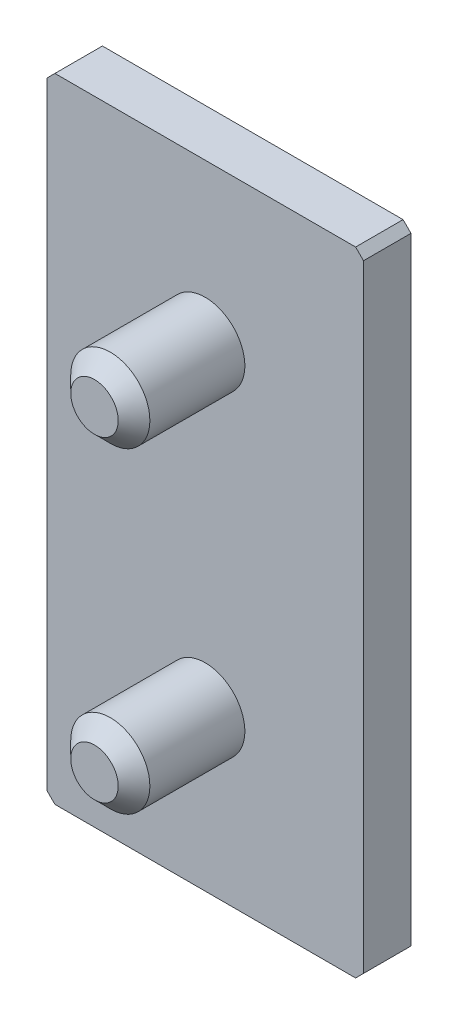
SolidWorks part; units mm, degrees
ref_plane "Front Plane" through (0, 0, 0) normal (0, 0, 1) x (1, 0, 0)
ref_plane "Top Plane" through (0, 0, 0) normal (0, 1, 0) x (1, 0, 0)
ref_plane "Right Plane" through (0, 0, 0) normal (1, 0, 0) x (0, 0, -1)
sketch "Sketch1" plane through (0, 0, 0) normal (0, 0, 1) x (1, 0, 0)
  line L1 (0, 0) -> (20, 0)
  line L2 (0, 0) -> (0, 40)
  line L3 (0, 40) -> (20, 40)
  line L4 (20, 0) -> (20, 40)
  dimension "D1" = 20
  dimension "D2" = 40
extrude "Boss-Extrude1" add sketch "Sketch1" along normal blind 3
sketch "Sketch2" plane through (0, 0, 3) normal (0, 0, 1) x (1, 0, 0)
  line L0 (20, 40) -> (0, 40) construction
  line L1 (20, 0) -> (20, 40) construction
  line L2 (0, 0) -> (20, 0) construction
  line L3 (0, 40) -> (0, 0) construction
  circle A0 centre (10, 30) radius 2.5
  circle A1 centre (10, 10) radius 2.5
  dimension "D1" = 10
  dimension "D6" = 5
  dimension "D7" = 5
  dimension "D2" = 10
  dimension "D3" = 10
  dimension "D4" = 10
  dimension "D5" = 20
extrude "Boss-Extrude2" add sketch "Sketch2" along normal blind 7
chamfer "Chamfer1" distance 1 angle 45 2 edges at (12.5, 10, 10) (12.5, 30, 10)
chamfer "Chamfer2" distance 0.5 angle 45 4 edges at (0, 0, 1.5) (20, 0, 1.5) (0, 40, 1.5) (20, 40, 1.5)
